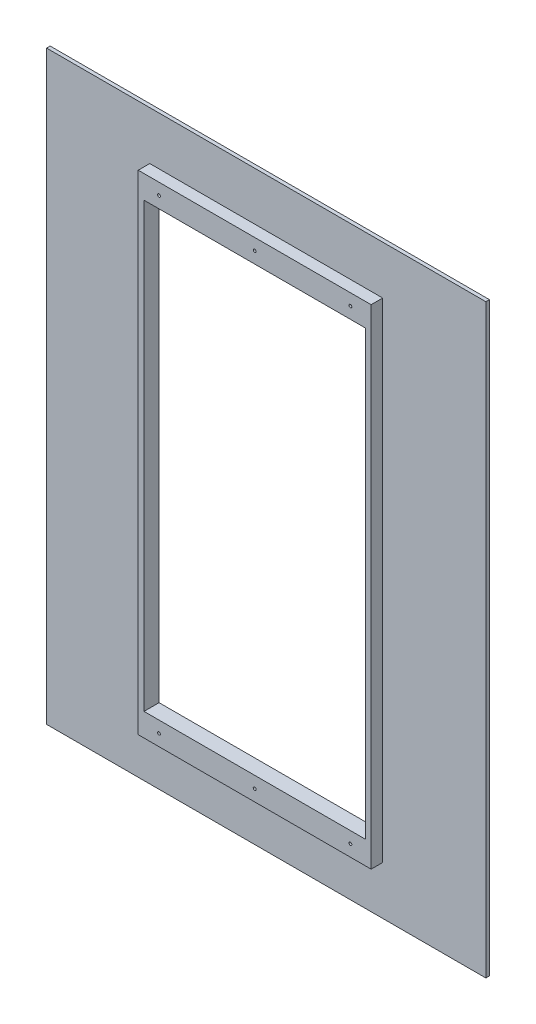
SolidWorks part; units mm, degrees
ref_plane "Front Plane" through (0, 0, 0) normal (0, 0, 1) x (1, 0, 0)
ref_plane "Top Plane" through (0, 0, 0) normal (0, 1, 0) x (1, 0, 0)
ref_plane "Right Plane" through (0, 0, 0) normal (1, 0, 0) x (0, 0, -1)
sketch "Sketch1" plane through (0, 0, 0) normal (0, 0, 1) x (1, 0, 0)
  line L1 (0, 0) -> (381, 0)
  line L2 (0, 0) -> (0, 508)
  line L3 (0, 508) -> (381, 508)
  line L4 (381, 0) -> (381, 508)
  line L5 (94.5, 446) -> (286.5, 446)
  line L6 (94.5, 446) -> (94.5, 62)
  line L7 (94.5, 62) -> (286.5, 62)
  line L8 (286.5, 446) -> (286.5, 62)
  dimension "D1" = 381
  dimension "D2" = 508
  dimension "D3" = 192
  dimension "D4" = 384
  dimension "D5" = 62
  dimension "D6" = 94.5
extrude "Boss-Extrude1" add sketch "Sketch1" along normal blind 13.1
ref_plane "Plane1" through (190.5, 0, 0) normal (-1, 0, 0) x (0, 0, 1)
ref_plane "Plane2" through (0, 254, 0) normal (0, 1, 0) x (1, 0, 0)
sketch "Sketch11" plane through (0, 0, 13.1) normal (0, 0, 1) x (1, 0, 0)
  line L0 (381, 508) -> (0, 508) construction
  line L1 (0, 508) -> (0, 0) construction
  circle A0 centre (107.5, 456) radius 1.25
  dimension "D1" = 52
  dimension "D2" = 107.5
extrude "Cut-Extrude4" cut sketch "Sketch11" against normal blind 10
sketch "Sketch12" plane through (0, 0, 13.1) normal (0, 0, 1) x (1, 0, 0)
  line L0 (381, 508) -> (0, 508) construction
  line L1 (381, 0) -> (381, 508) construction
  line L2 (0, 0) -> (381, 0) construction
  line L3 (0, 508) -> (0, 0) construction
  circle A0 centre (273.5, 456) radius 1.25
  circle A1 centre (107.5, 52) radius 1.25
  circle A2 centre (273.5, 52) radius 1.25
  dimension "D1" = 52
  dimension "D2" = 107.5
  dimension "D3" = 52
  dimension "D5" = 52
  dimension "D6" = 107.5
  dimension "D4" = 107.5
extrude "Cut-Extrude5" cut sketch "Sketch12" against normal blind 10
sketch "Sketch19" plane through (0, 0, 13.1) normal (0, 0, 1) x (1, 0, 0)
  line L0 (190.5, 7.205) -> (190.5, -7.205) construction
  line L1 (381, 508) -> (0, 508) construction
  line L3 (0, 0) -> (381, 0) construction
  circle A0 centre (190.5, 456) radius 1.25
  circle A1 centre (190.5, 52) radius 1.25
  dimension "D1" = 52
  dimension "D2" = 52
extrude "Cut-Extrude6" cut sketch "Sketch19" against normal blind 10
sketch "Sketch20" plane through (0, 0, 13.1) normal (0, 0, 1) x (1, 0, 0)
  line L0 (0, 0) -> (381, 0) construction
  line L1 (0, 508) -> (89.5, 508)
  line L2 (0, 508) -> (0, 0)
  line L3 (0, 0) -> (89.5, 0)
  line L4 (89.5, 508) -> (89.5, 0)
  line L5 (94.5, 446) -> (94.5, 62) construction
  line L6 (286.5, 62) -> (286.5, 446) construction
  line L7 (381, 508) -> (291.5, 508)
  line L8 (381, 508) -> (381, 0)
  line L9 (381, 0) -> (291.5, 0)
  line L10 (291.5, 508) -> (291.5, 0)
  dimension "D1" = 5
  dimension "D2" = 5
extrude "Cut-Extrude7" cut sketch "Sketch20" against normal blind 10
sketch "Sketch21" plane through (0, 0, 13.1) normal (0, 0, 1) x (1, 0, 0)
  line L0 (291.5, 508) -> (291.5, 0) construction
  line L1 (89.5, 508) -> (291.5, 508)
  line L2 (89.5, 508) -> (89.5, 466)
  line L3 (89.5, 466) -> (291.5, 466)
  line L4 (291.5, 508) -> (291.5, 466)
  line L5 (291.5, 508) -> (291.5, 0) construction
  line L6 (89.5, 0) -> (291.5, 0)
  line L7 (89.5, 0) -> (89.5, 42)
  line L8 (89.5, 42) -> (291.5, 42)
  line L9 (291.5, 0) -> (291.5, 42)
  dimension "D1" = 42
  dimension "D2" = 42
extrude "Cut-Extrude8" cut sketch "Sketch21" against normal blind 10
